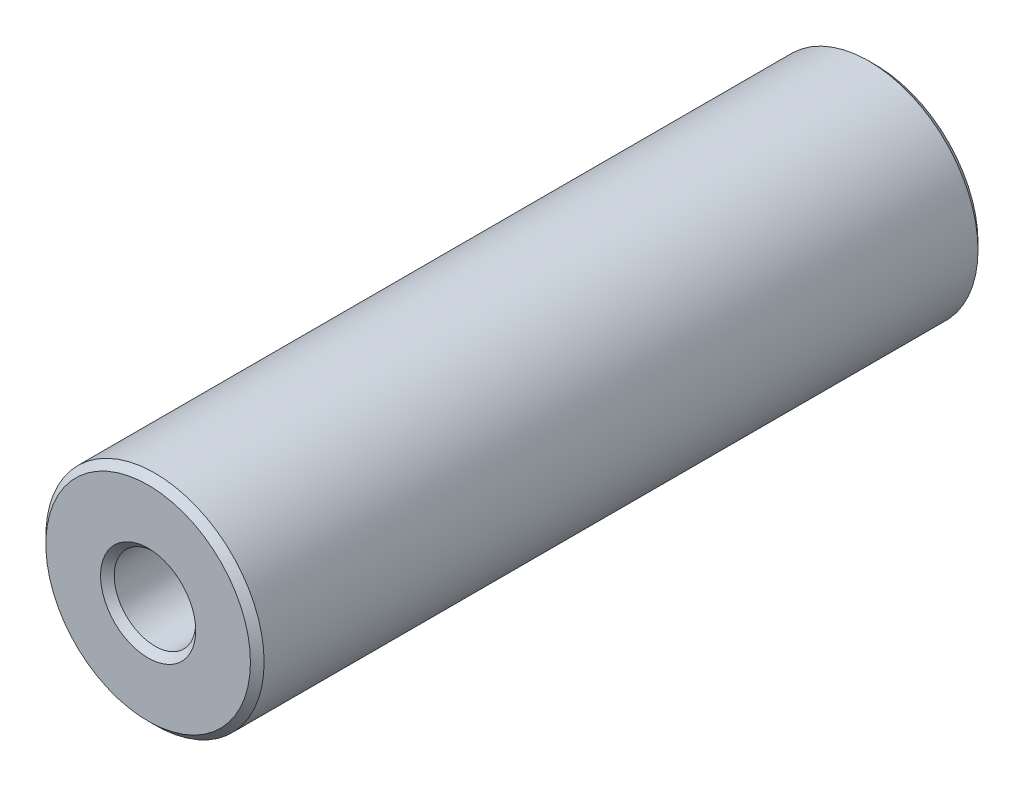
SolidWorks part; units mm, degrees
ref_plane "Front Plane" through (0, 0, 0) normal (0, 0, 1) x (1, 0, 0)
ref_plane "Top Plane" through (0, 0, 0) normal (0, 1, 0) x (1, 0, 0)
ref_plane "Right Plane" through (0, 0, 0) normal (1, 0, 0) x (0, 0, -1)
sketch "Sketch1" plane through (0, 0, 0) normal (0, 0, 1) x (1, 0, 0)
  circle A0 centre (0, 0) radius 4.7625 construction
  circle A1 centre (0, 0) radius 1.778 construction
  point P4 (0, 4.7625)
  dimension "ID" = 3.556
  dimension "OD" = 9.525
sketch "Sketch2" plane through (0, 0, 0) normal (1, 0, 0) x (0, 0, -1)
  line L0 (-15.875, 4.7625) -> (15.875, 4.7625) construction
  dimension "Length" = 31.75
sketch "Sketch3" plane through (0, 0, 0) normal (0, 0, 1) x (1, 0, 0)
  circle A0 centre (0, 0) radius 1.778 construction
  circle A1 centre (0, 0) radius 4.7625 construction
  circle A2 centre (0, 0) radius 1.778
  circle A3 centre (0, 0) radius 4.7625
extrude "Boss-Extrude1" add sketch "Sketch3" against normal up to vertex (15.875 mm away) and the other way up to vertex (15.875 mm away) up to point (0, 4.7625, -15.875) other way up to point (0, 4.7625, 15.875)
chamfer "Chamfer1" distance 0.2984 angle 45 4 edges at (4.7625, 0, 15.875) (4.7625, 0, -15.875) (1.778, 0, 15.875) (1.778, 0, -15.875)
equation "\"D1@Chamfer1\"=(\"OD@Sketch1\"-\"ID@Sketch1\")*0.05"
